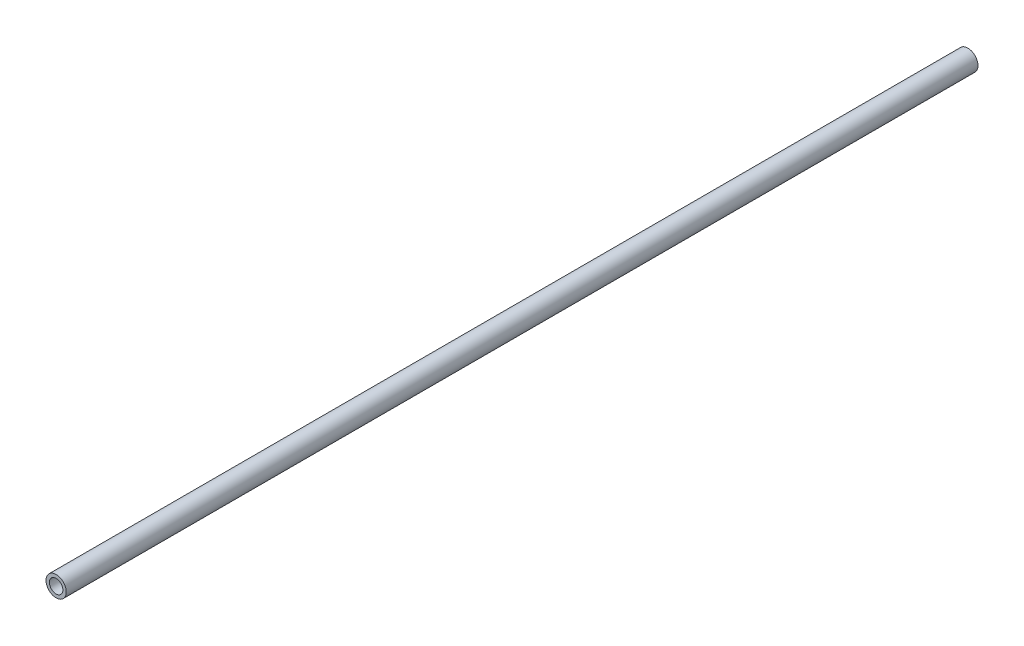
SolidWorks part; units mm, degrees
ref_plane "Front Plane" through (0, 0, 0) normal (0, 0, 1) x (1, 0, 0)
ref_plane "Top Plane" through (0, 0, 0) normal (0, 1, 0) x (1, 0, 0)
ref_plane "Right Plane" through (0, 0, 0) normal (1, 0, 0) x (0, 0, -1)
sketch "Sketch1" plane through (0, 0, 0) normal (0, 0, 1) x (1, 0, 0)
  circle A0 centre (0, 0) radius 3
  circle A1 centre (0, 0) radius 2
  dimension "D1" = 6
  dimension "D2" = 4
extrude "Boss-Extrude1" add sketch "Sketch1" along normal blind 270
